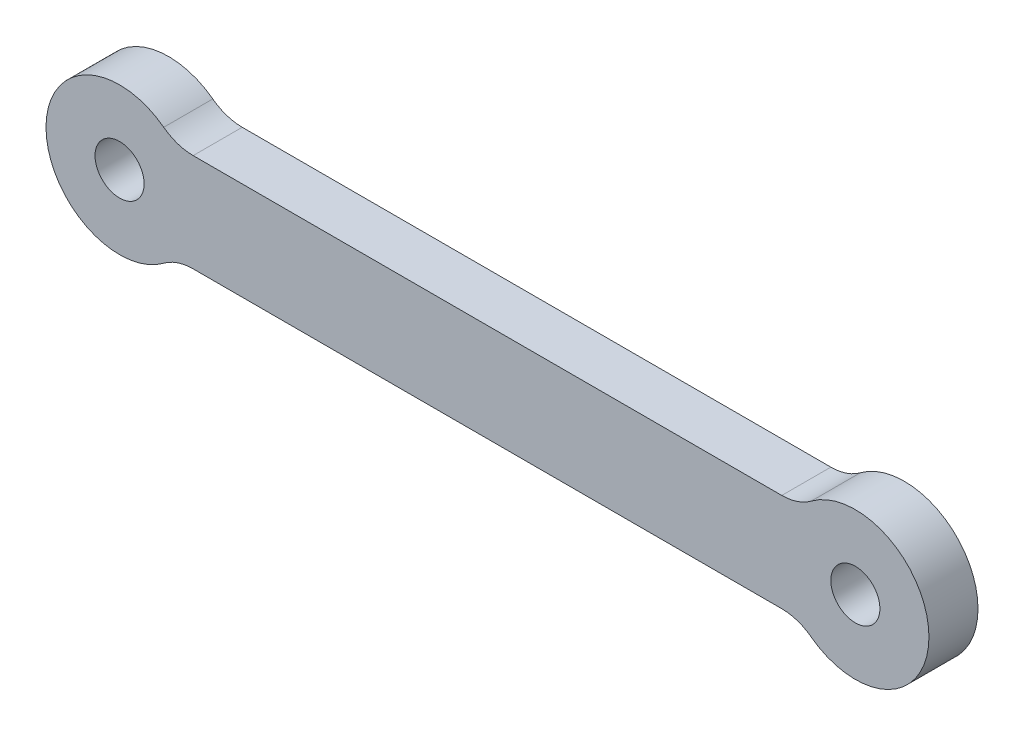
SolidWorks part; units mm, degrees
ref_plane "Front Plane" through (0, 0, 0) normal (0, 0, 1) x (1, 0, 0)
ref_plane "Top Plane" through (0, 0, 0) normal (0, 1, 0) x (1, 0, 0)
ref_plane "Right Plane" through (0, 0, 0) normal (1, 0, 0) x (0, 0, -1)
sketch "Sketch1" plane through (0, 0, 0) normal (0, 0, 1) x (1, 0, 0)
  line L0 (0, -2) -> (0, 2)
  line L1 (0, 2) -> (12, 2)
  line L2 (12, -2) -> (0, -2)
  line L3 (0, 0) -> (23.8386, 0) construction
  circle A0 centre (15, 0) radius 1
  arc A1 (12, 2) -> (13.2, 2.4) centre (12, 4) ccw
  arc A2 (13.2, 2.4) -> (13.2, -2.4) centre (15, 0) cw
  arc A3 (13.2, -2.4) -> (12, -2) centre (12, -4) ccw
  dimension "D2" = 2
  dimension "D4" = 3
  dimension "D5" = 2
  dimension "D1" = 4
  dimension "D3" = 15
extrude "Boss-Extrude1" add sketch "Sketch1" along normal blind 2 contours L1 A1 A2 A3 L2 L0 | A0
mirror "Mirror1" about plane through (0, -2, 2) normal (-1, 0, 0) of "Boss-Extrude1"
